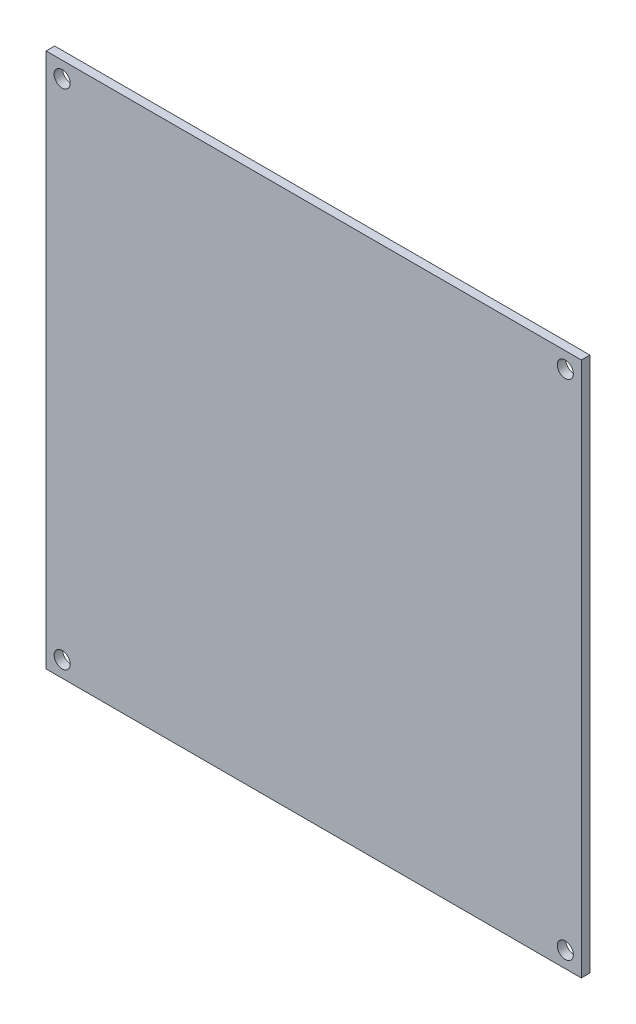
SolidWorks part; units mm, degrees
ref_plane "前视基准面" through (0, 0, 0) normal (0, 0, 1) x (1, 0, 0)
ref_plane "上视基准面" through (0, 0, 0) normal (0, 1, 0) x (1, 0, 0)
ref_plane "右视基准面" through (0, 0, 0) normal (1, 0, 0) x (0, 0, -1)
sketch "草图1" plane through (0, 0, 0) normal (0, 0, 1) x (1, 0, 0)
  line L1 (0, 0) -> (100, 0)
  line L2 (0, 0) -> (0, 100)
  line L3 (0, 100) -> (100, 100)
  line L4 (100, 0) -> (100, 100)
  circle A0 centre (3, 3) radius 1.5
  circle A1 centre (97, 3) radius 1.5
  circle A2 centre (97, 97) radius 1.5
  circle A3 centre (3, 97) radius 1.5
  dimension "D3" = 3
  dimension "D6" = 3
  dimension "D9" = 3
  dimension "D14" = 3
  dimension "D1" = 100
  dimension "D2" = 100
  dimension "D4" = 3
  dimension "D5" = 3
  dimension "D7" = 3
  dimension "D8" = 3
  dimension "D10" = 3
  dimension "D11" = 3
  dimension "D12" = 3
  dimension "D13" = 3
extrude "凸台-拉伸1" add sketch "草图1" along normal blind 1.6
